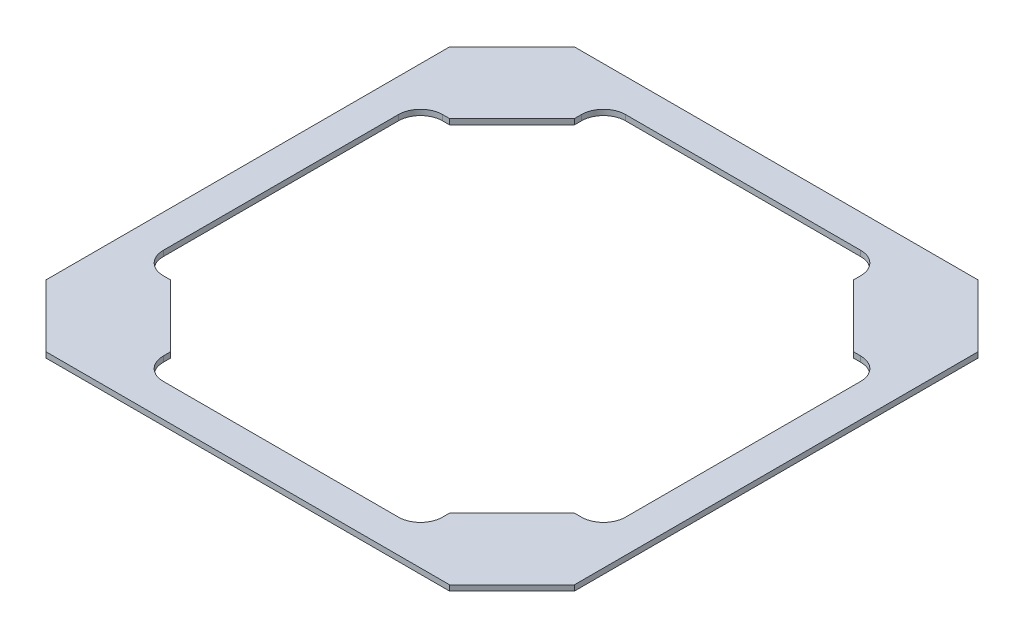
SolidWorks part; units mm, degrees
ref_plane "Front Plane" through (0, 0, 0) normal (0, 0, 1) x (1, 0, 0)
ref_plane "Top Plane" through (0, 0, 0) normal (0, 1, 0) x (1, 0, 0)
ref_plane "Right Plane" through (0, 0, 0) normal (1, 0, 0) x (0, 0, -1)
sketch "Sketch2" plane through (0, 0, 0) normal (0, 1, 0) x (1, 0, 0)
  line L0 (-152.4, 116.479) -> (-116.479, 152.4)
  line L1 (-116.479, 152.4) -> (116.479, 152.4)
  line L2 (-152.4, 116.479) -> (-152.4, -116.479)
  line L3 (-116.479, 80.558) -> (-80.558, 116.479)
  line L4 (-134.4395, 134.4395) -> (-98.5185, 98.5185) construction
  line L5 (-67.858, 133.35) -> (67.858, 133.35)
  line L6 (-133.35, 67.858) -> (-133.35, -67.858)
  line L7 (-116.479, 80.558) -> (-120.65, 80.558)
  line L8 (-80.558, 116.479) -> (-80.558, 120.65)
  line L9 (0, 0) -> (0, 208.1331) construction
  line L10 (0, 0) -> (-190.1851, 0) construction
  line L11 (133.35, 67.858) -> (133.35, -67.858)
  line L12 (152.4, 116.479) -> (152.4, -116.479)
  line L13 (134.4395, 134.4395) -> (98.5185, 98.5185) construction
  line L14 (80.558, 116.479) -> (80.558, 120.65)
  line L15 (116.479, 80.558) -> (120.65, 80.558)
  line L16 (116.479, 80.558) -> (80.558, 116.479)
  line L17 (152.4, 116.479) -> (116.479, 152.4)
  line L18 (134.4395, -134.4395) -> (98.5185, -98.5185) construction
  line L19 (-134.4395, -134.4395) -> (-98.5185, -98.5185) construction
  line L20 (152.4, -116.479) -> (116.479, -152.4)
  line L21 (116.479, -80.558) -> (80.558, -116.479)
  line L22 (116.479, -80.558) -> (120.65, -80.558)
  line L23 (80.558, -116.479) -> (80.558, -120.65)
  line L24 (-80.558, -116.479) -> (-80.558, -120.65)
  line L25 (-116.479, -80.558) -> (-120.65, -80.558)
  line L26 (-67.858, -133.35) -> (67.858, -133.35)
  line L27 (-116.479, -80.558) -> (-80.558, -116.479)
  line L28 (-116.479, -152.4) -> (116.479, -152.4)
  line L29 (-152.4, -116.479) -> (-116.479, -152.4)
  arc A0 (-80.558, 120.65) -> (-67.858, 133.35) centre (-67.858, 120.65) cw
  arc A1 (-120.65, 80.558) -> (-133.35, 67.858) centre (-120.65, 67.858) ccw
  arc A2 (120.65, 80.558) -> (133.35, 67.858) centre (120.65, 67.858) cw
  arc A3 (80.558, 120.65) -> (67.858, 133.35) centre (67.858, 120.65) ccw
  arc A4 (80.558, -120.65) -> (67.858, -133.35) centre (67.858, -120.65) cw
  arc A5 (120.65, -80.558) -> (133.35, -67.858) centre (120.65, -67.858) ccw
  arc A6 (-120.65, -80.558) -> (-133.35, -67.858) centre (-120.65, -67.858) cw
  arc A7 (-80.558, -120.65) -> (-67.858, -133.35) centre (-67.858, -120.65) ccw
  point P23 (133.35, 0)
  point P25 (0, 133.35)
  point P26 (0, 152.4)
  point P54 (152.4, 0)
  point P56 (-133.35, 0)
  point P57 (-152.4, 0)
  point P58 (0, -152.4)
  point P59 (0, -133.35)
  dimension "D10" = 12.7
  dimension "D1" = 50.8
  dimension "D2" = 152.4
  dimension "D3" = 152.4
  dimension "D4" = 50.8
  dimension "D5" = 19.05
  dimension "D6" = 19.05
  dimension "D7" = 45
  dimension "D8" = 45
  dimension "D9" = 50.8
extrude "Boss-Extrude1" add sketch "Sketch2" along normal blind 3.175
